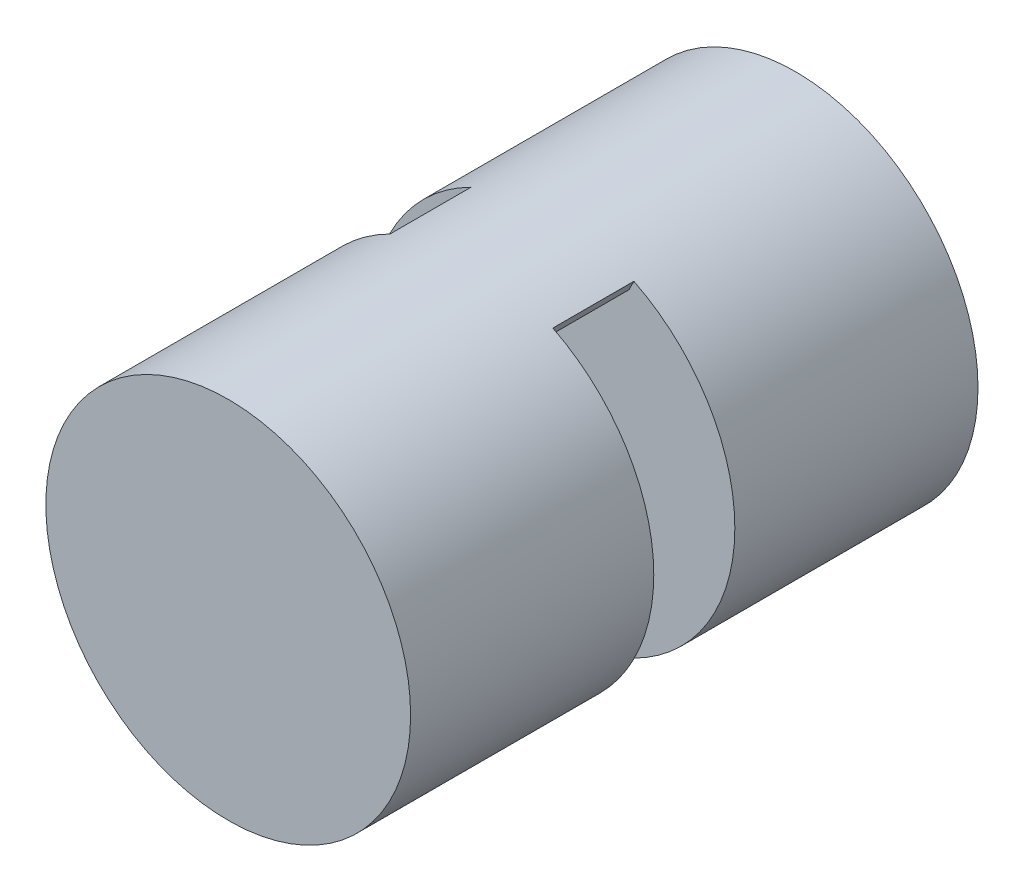
SolidWorks part; units mm, degrees
ref_plane "前视基准面" through (0, 0, 0) normal (0, 0, 1) x (1, 0, 0)
ref_plane "上视基准面" through (0, 0, 0) normal (0, 1, 0) x (1, 0, 0)
ref_plane "右视基准面" through (0, 0, 0) normal (1, 0, 0) x (0, 0, -1)
sketch "草图1" plane through (0, 0, 0) normal (0, 0, 1) x (1, 0, 0)
  circle A0 centre (0, 0) radius 22.5
extrude "凸台-拉伸1" add sketch "草图1" along normal blind 30
sketch "草图3" plane through (0, 0, 30) normal (0, 0, 1) x (1, 0, 0)
  line L0 (-10.0485, 20.1315) -> (-9.4473, 18.9269)
  line L1 (10.0485, 20.1315) -> (9.4473, 18.9269)
  line L2 (-10.0485, -20.1315) -> (-9.4473, -18.9269)
  line L3 (10.0485, -20.1315) -> (9.4473, -18.9269)
  arc A0 (-10.0485, -20.1315) -> (10.0485, -20.1315) centre (0, 0) ccw
  arc A1 (9.4473, 18.9269) -> (-9.4473, 18.9269) centre (0, 0) ccw
  arc A2 (10.0485, 20.1315) -> (-10.0485, 20.1315) centre (0, 0) ccw
  arc A3 (-9.4473, -18.9269) -> (9.4473, -18.9269) centre (0, 0) ccw
extrude "凸台-拉伸2" add sketch "草图3" along normal blind 10
sketch "草图4" plane through (0, 0, 40) normal (0, 0, 1) x (1, 0, 0)
  circle A0 centre (0, 0) radius 22.5
extrude "凸台-拉伸3" add sketch "草图4" along normal blind 30
